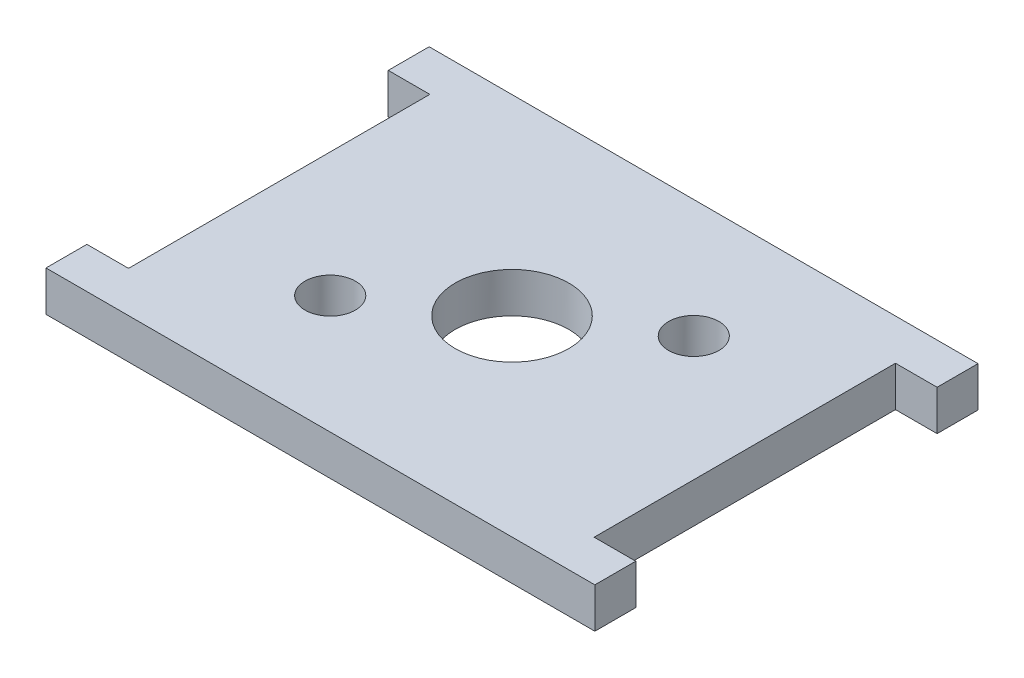
SolidWorks part; units mm, degrees
material "Motor Mount Side"
ref_plane "Front Plane" through (0, 0, 0) normal (0, 0, 1) x (1, 0, 0)
ref_plane "Top Plane" through (0, 0, 0) normal (0, 1, 0) x (1, 0, 0)
ref_plane "Right Plane" through (0, 0, 0) normal (1, 0, 0) x (0, 0, -1)
sketch "Sketch1" plane through (0, 0, 0) normal (0, 1, 0) x (1, 0, 0)
  line L1 (0, 0) -> (39.878, 0)
  line L2 (0, 0) -> (0, 27.8384)
  line L3 (0, 27.8384) -> (39.878, 27.8384)
  line L4 (39.878, 0) -> (39.878, 27.8384)
  dimension "D1" = 39.878
  dimension "D2" = 27.8384
extrude "Boss-Extrude1" add sketch "Sketch1" along normal blind 2.921
sketch "Sketch3" plane through (0, 2.921, 0) normal (0, 1, 0) x (1, 0, 0)
  line L0 (0, 27.8384) -> (0, 0) construction
  line L1 (0, 24.8666) -> (3.0226, 24.8666)
  line L2 (0, 24.8666) -> (0, 2.9718)
  line L3 (0, 2.9718) -> (3.0226, 2.9718)
  line L4 (3.0226, 24.8666) -> (3.0226, 2.9718)
  line L5 (1.5113, 24.8666) -> (1.5113, 27.8384) construction
  line L6 (39.878, 27.8384) -> (0, 27.8384) construction
  line L7 (1.5113, 2.9718) -> (1.5113, 0) construction
  line L8 (0, 0) -> (39.878, 0) construction
  line L9 (19.939, 27.8384) -> (19.939, 0) construction
  line L10 (39.878, 24.8666) -> (39.878, 2.9718)
  line L11 (39.878, 2.9718) -> (36.8554, 2.9718)
  line L12 (39.878, 24.8666) -> (36.8554, 24.8666)
  line L13 (36.8554, 24.8666) -> (36.8554, 2.9718)
  dimension "D1" = 3.0226
  dimension "D2" = 21.8948
extrude "Cut-Extrude2" cut sketch "Sketch3" against normal up to next
sketch "Sketch2" plane through (0, 2.921, 0) normal (0, 1, 0) x (1, 0, 0)
  line L0 (19.939, 27.8384) -> (19.939, 0) construction
  line L1 (39.878, 27.8384) -> (0, 27.8384) construction
  line L2 (0, 0) -> (39.878, 0) construction
  line L3 (12.065, 10.414) -> (30.758, 10.414) construction
  line L6 (10.2362, 8.5852) -> (10.2362, -5.4141) construction
  line L8 (12.065, 8.5852) -> (3.0226, 8.5852) construction
  line L9 (27.813, 19.2532) -> (36.8554, 19.2532) construction
  line L11 (27.813, 27.8384) -> (27.813, 19.2532) construction
  line L12 (12.065, 8.5852) -> (12.065, 0) construction
  line L13 (3.0226, 2.9718) -> (3.0226, 24.8666) construction
  line L14 (36.8554, 24.8666) -> (36.8554, 2.9718) construction
  circle A0 centre (19.939, 13.9192) radius 4.1275
  circle A1 centre (12.065, 8.5852) radius 1.8288
  circle A2 centre (27.813, 19.2532) radius 1.8288
  dimension "D1" = 8.255
  dimension "D2" = 3.6576
  dimension "D3" = 17.4244
  dimension "D4" = 7.2136
extrude "Cut-Extrude1" cut sketch "Sketch2" against normal up to next
